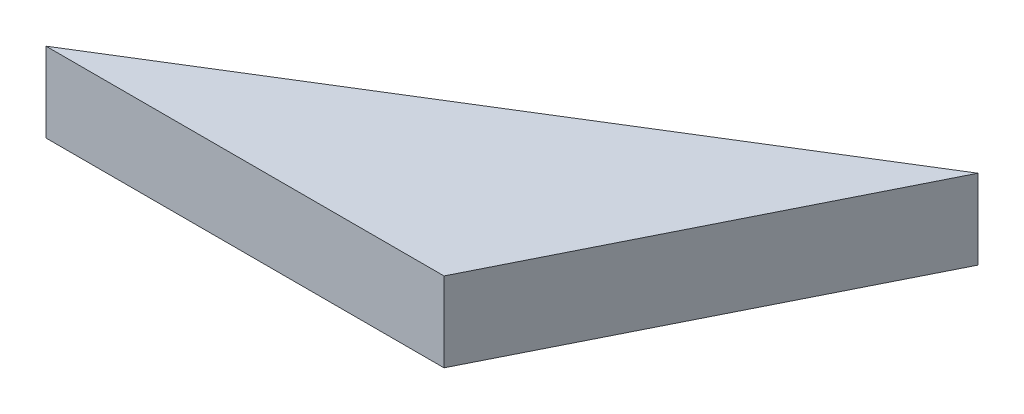
SolidWorks part; units mm, degrees
ref_plane "Front Plane" through (0, 0, 0) normal (0, 0, 1) x (1, 0, 0)
ref_plane "Top Plane" through (0, 0, 0) normal (0, 1, 0) x (1, 0, 0)
ref_plane "Right Plane" through (0, 0, 0) normal (1, 0, 0) x (0, 0, -1)
sketch "Sketch1" plane through (0, 0, 0) normal (0, 1, 0) x (1, 0, 0)
  line L0 (0, 0) -> (-30, 0)
  line L1 (0, 0) -> (13.4187, 26.8317)
  line L2 (13.4187, 26.8317) -> (-30, 0)
extrude "Boss-Extrude1" add sketch "Sketch1" along normal blind 6 contours L1 L2 L0
